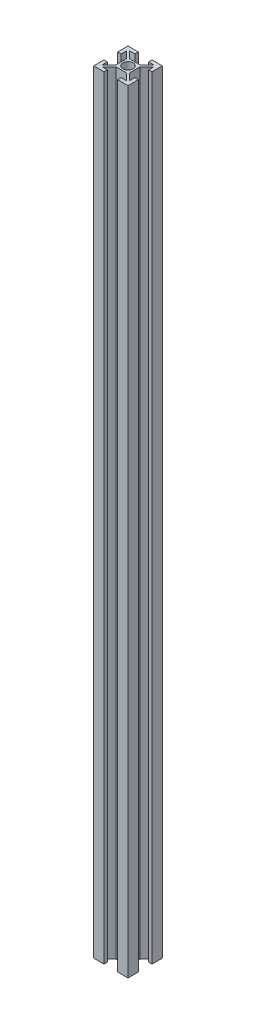
SolidWorks part; units mm, degrees
material "1060 Alloy"
ref_plane "Front Plane" through (0, 0, 0) normal (0, 0, 1) x (1, 0, 0)
ref_plane "Top Plane" through (0, 0, 0) normal (0, 1, 0) x (1, 0, 0)
ref_plane "Right Plane" through (0, 0, 0) normal (1, 0, 0) x (0, 0, -1)
sketch "Sketch1" plane through (0, 0, 0) normal (0, 0, 1) x (1, 0, 0)
  line L0 (18.2498, -12.1687) -> (243.1097, 212.6913) construction
  line L1 (243.1097, 212.6913) -> (18.2498, 437.5512) construction
  dimension "D1" = 318
  dimension "D2" = 318
  dimension "D3" = 90
sketch "2020 sketch" plane through (0, 0, 0) normal (0, 1, 0) x (1, 0, 0)
  line L0 (-4, 10) -> (-4, 8)
  line L1 (-10, 10) -> (-4, 10)
  line L2 (-10, 10) -> (-10, 4)
  line L3 (-10, -10) -> (-4, -10)
  line L4 (10, 10) -> (10, 4)
  line L5 (-10, 10) -> (10, -10) construction
  line L6 (-10, -10) -> (10, 10) construction
  line L7 (-4, 8) -> (-7, 8)
  line L8 (-7, 8) -> (-3, 4)
  line L9 (-3, 4) -> (3, 4)
  line L10 (3, 4) -> (7, 8)
  line L11 (7, 8) -> (4, 8)
  line L12 (4, 8) -> (4, 10)
  line L13 (4, 3) -> (4, -3)
  line L14 (8, 7) -> (4, 3)
  line L15 (8, 4) -> (8, 7)
  line L16 (10, 4) -> (8, 4)
  line L17 (8, -4) -> (10, -4)
  line L18 (8, -7) -> (8, -4)
  line L19 (4, -3) -> (8, -7)
  line L20 (3, -4) -> (-3, -4)
  line L21 (7, -8) -> (3, -4)
  line L22 (4, -8) -> (7, -8)
  line L23 (4, -10) -> (4, -8)
  line L24 (-4, -8) -> (-4, -10)
  line L25 (-7, -8) -> (-4, -8)
  line L26 (-3, -4) -> (-7, -8)
  line L27 (-4, -3) -> (-4, 3)
  line L28 (-8, -7) -> (-4, -3)
  line L29 (-8, -4) -> (-8, -7)
  line L30 (-10, -4) -> (-8, -4)
  line L31 (-8, 4) -> (-10, 4)
  line L32 (-8, 7) -> (-8, 4)
  line L33 (-4, 3) -> (-8, 7)
  line L34 (-10, -4) -> (-10, -10)
  line L35 (10, -4) -> (10, -10)
  line L36 (4, 10) -> (10, 10)
  line L37 (4, -10) -> (10, -10)
  circle A0 centre (0, 0) radius 3
  point P0 (0, 0)
  point P14 (4, 9)
  point P42 (0, 0)
  dimension "D9" = 6
  dimension "D1" = 20
  dimension "D2" = 20
  dimension "D3" = 8
  dimension "D4" = 6
  dimension "D5" = 6
  dimension "D6" = 2
  dimension "D7" = 4
  dimension "D8" = 4
extrude "Boss-Extrude1" add sketch "2020 sketch" along normal blind 450 from vertex at -12.1687 contours A0 | L28 L27 L33 L32 L31 L2 L1 L0 L7 L8 L9 L10 L11 L12 L36 L4 L16 L15 L14 L13 L19 L18 L17 L35 L37 L23 L22 L21 L20 L26 L25 L24 L3 L34 L30 L29
